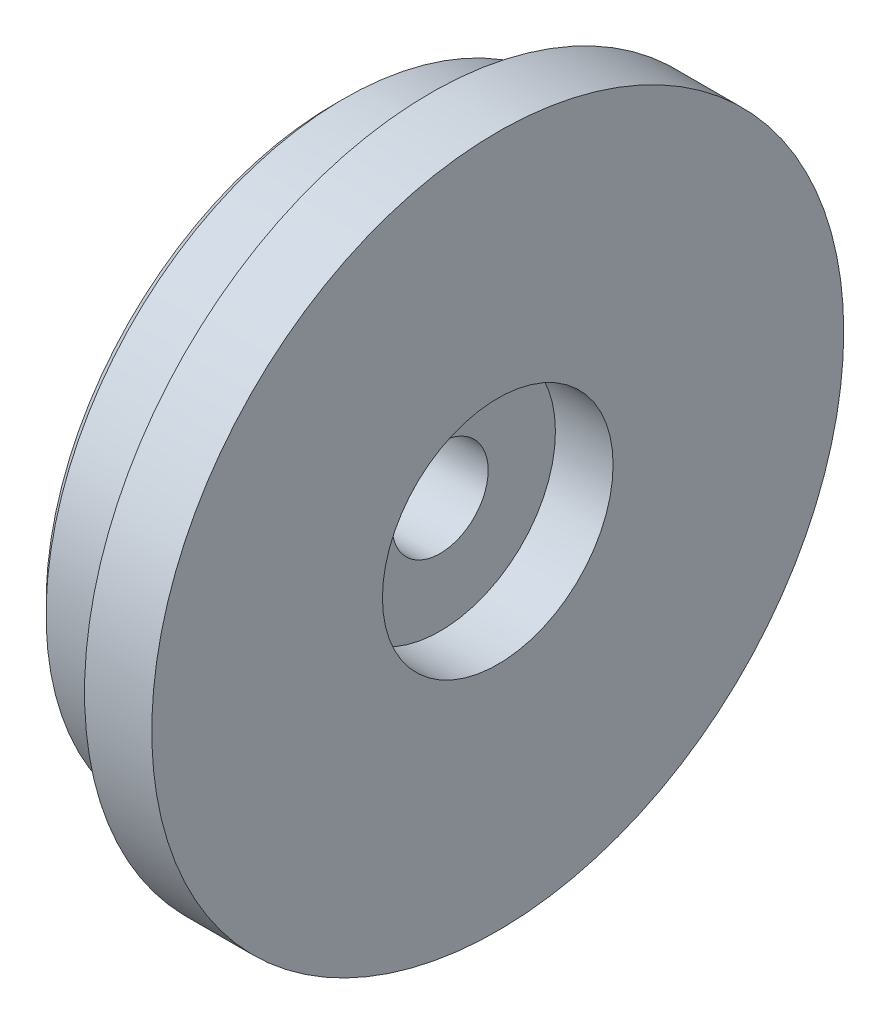
SolidWorks part; units mm, degrees
ref_plane "Plan de face" through (0, 0, 0) normal (0, 0, 1) x (1, 0, 0)
ref_plane "Plan de dessus" through (0, 0, 0) normal (0, 1, 0) x (1, 0, 0)
ref_plane "Plan de droite" through (0, 0, 0) normal (1, 0, 0) x (0, 0, -1)
sketch "Esquisse1" plane through (0, 0, 0) normal (0, 0, 1) x (1, 0, 0)
  line L0 (0, 0) -> (0, 18) construction
  line L1 (0, 18) -> (-3.5, 18)
  line L2 (0, 18) -> (0, 6)
  line L3 (-3.5, 18) -> (-3.5, 15)
  line L4 (-3.5, 15) -> (-4.5, 15)
  line L5 (-4.5, 15) -> (-4.5, 15.5)
  line L6 (-4.5, 15.5) -> (-8, 15.5)
  line L8 (0, 6) -> (-3, 6)
  line L9 (-3, 6) -> (-3, 2.5)
  line L10 (-3, 2.5) -> (-8.5, 2.5)
  line L11 (-8, 15.5) -> (-8.5, 15)
  line L12 (-8.5, 2.5) -> (-8.5, 5)
  line L13 (-8.5, 5) -> (-5.75, 5)
  line L14 (-5, 5.75) -> (-5, 11.25)
  line L15 (-5.75, 12) -> (-8.5, 12)
  line L16 (-8.5, 12) -> (-8.5, 15)
  line L17 (-5, 11.25) -> (-5.75, 12)
  line L18 (-5.75, 5) -> (-5, 5.75)
  line L19 (0, 0) -> (-8.5, 0) construction
  point P8 (-8.5, 15.5)
  point P13 (-5, 5)
  point P15 (-5, 12)
  point P22 (0, 0)
  dimension "D1" = 18
  dimension "D2" = 3.5
  dimension "D3" = 12
  dimension "D4" = 3
  dimension "D5" = 1
  dimension "D6" = 0.5
  dimension "D8" = 2.5
  dimension "D9" = 3
  dimension "D10" = 3.5
  dimension "D11" = 5.5
  dimension "D12" = 3.5
  dimension "D14" = 7
  dimension "D15" = 3
  dimension "D16" = 3.5
revolve "Révolution1789" add sketch "Esquisse1" angle 360 about L19
cosmetic thread "Représentation de filetage1" parameters "D2"=30
cosmetic thread "Représentation de filetage2" parameters "D2"=6
